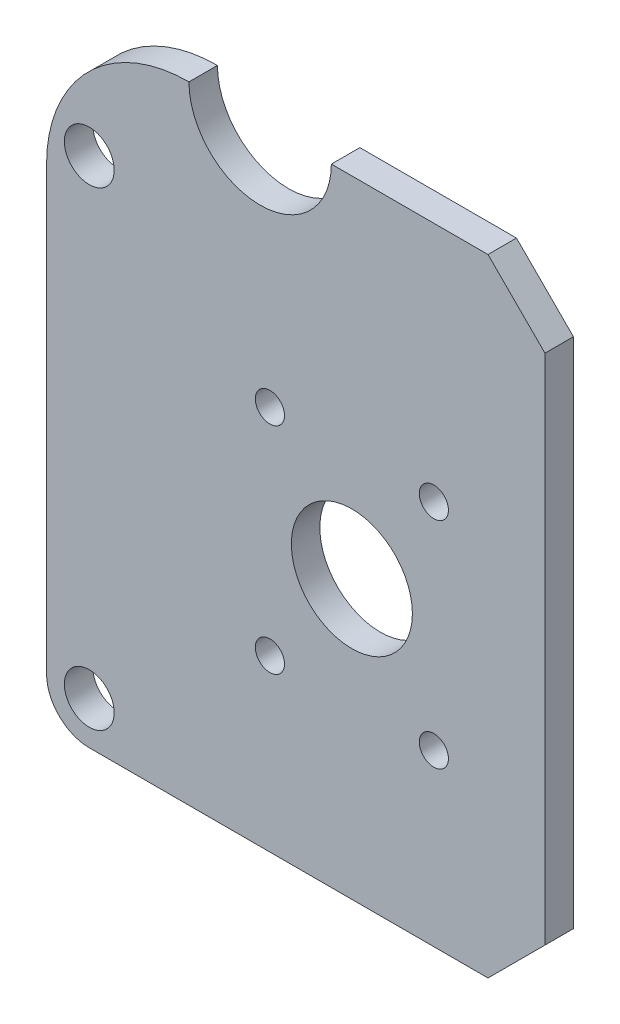
SolidWorks part; units mm, degrees
material "6061-T6 (SS)"
ref_plane "前视基准面" through (0, 0, 0) normal (0, 0, 1) x (1, 0, 0)
ref_plane "上视基准面" through (0, 0, 0) normal (0, 1, 0) x (1, 0, 0)
ref_plane "右视基准面" through (0, 0, 0) normal (1, 0, 0) x (0, 0, -1)
sketch "草图2" plane through (0, 0, 0) normal (0, 0, 1) x (1, 0, 0)
  line L0 (0, 19.5) -> (0, -19.5) construction
  line L1 (-18.5, 19.5) -> (18.5, 19.5)
  line L2 (-18.5, 19.5) -> (-18.5, -19.5)
  line L3 (-18.5, -19.5) -> (18.5, -19.5)
  line L4 (18.5, 19.5) -> (18.5, -19.5)
  dimension "D1" = 37
  dimension "D2" = 39
extrude "拉伸1" add sketch "草图2" along normal blind 2
sketch "草图3" plane through (0, 0, 2) normal (0, 0, 1) x (1, 0, 0)
  line L0 (-13.5, 16.5) -> (-13.5, -16.5) construction
  line L1 (0, 0) -> (-13.5, 0) construction
  line L2 (-18.5, 19.5) -> (-18.5, -19.5) construction
  circle A0 centre (-13.5, 16.5) radius 1.75
  circle A1 centre (-13.5, -16.5) radius 1.75
  dimension "D2" = 3.5
  dimension "D1" = 33
  dimension "D3" = 5
extrude "拉伸2" cut sketch "草图3" against normal blind 2
fillet "圆角1" [suppressed] radius 20
chamfer "倒角1" [suppressed] distance 22 angle 30
chamfer "倒角2" [suppressed] distance 22 angle 30
fillet "圆角2" [suppressed] radius 10
chamfer "倒角3" distance 1 angle 45 2 edges at (-18.5, -19.5, 1) (-18.5, 19.5, 1)
sketch "草图4" plane through (0, 0, 2) normal (0, 0, 1) x (1, 0, 0)
  line L0 (11.145, 5.2066) -> (-1.265, -5.2066) construction
  line L1 (4.94, 0) -> (4.94, 7.25) construction
  line L2 (-0.6138, 4.6602) -> (10.4938, -4.6602) construction
  line L3 (4.94, 0) -> (18.5, 0) construction
  line L5 (18.5, -19.5) -> (18.5, 19.5) construction
  circle A0 centre (4.94, 0) radius 8.1 construction
  circle A1 centre (4.94, 0) radius 7.25 construction
  circle A2 centre (-13.5, 16.5) radius 1.75 construction
  dimension "D1" = 16.2
  dimension "D2" = 14.5
  dimension "D3" = 50
  dimension "D4" = 50
  dimension "D5" = 18.44
hole_wizard "M1.6 螺纹孔1" [suppressed] positions "3D草图2" profile "草图6" tap size "M1.6" standard "GB"
sketch3d "3D草图2"
  point P3 (13.145, 5.2066, 2)
  point P6 (12.4938, -4.6602, 2)
  point P9 (0.735, -5.2066, 2)
  point P12 (1.3862, 4.6602, 2)
sketch "草图6" plane through (13.145, 5.2066, 2) normal (1, 0, 0) x (0, -1, 0)
  line L0 (0, 0) -> (0, 4.6255)
  line L1 (0, 4.6255) -> (0.625, 4.25)
  line L2 (0.625, 4.25) -> (0.625, 0)
  line L5 (0.625, 0) -> (0, 0)
  line L10 (0, 4.6255) -> (-0.625, 4.25) construction
  line L11 (0, -6.35) -> (0, 107.95) construction
  dimension "螺纹孔钻头直径" = 1.25
  dimension "螺纹孔钻头深度" = 4.25
  dimension "导头角度" = 118
cosmetic thread "Hole Thread1" [suppressed] parameters "D1"=2, "D2"=1.6
cosmetic thread "Hole Thread2" [suppressed] parameters "D1"=2, "D2"=1.6
cosmetic thread "Hole Thread3" [suppressed] parameters "D1"=2, "D2"=1.6
cosmetic thread "Hole Thread4" [suppressed] parameters "D1"=2, "D2"=1.6
sketch "草图7" plane through (0, 0, 2) normal (0, 0, 1) x (1, 0, 0)
  circle A0 centre (4.94, 0) radius 4.25
  dimension "D1" = 8.5
extrude "拉伸3" cut sketch "草图7" against normal blind 10
sketch "草图8" plane through (0, 0, 2) normal (0, 0, 1) x (1, 0, 0)
  line L0 (18.5, 19.5) -> (-17.5, 19.5) construction
  line L1 (-16.5, 19.5) -> (-18.5, 19.5)
  line L2 (-16.5, 19.5) -> (-16.5, -19.5)
  line L3 (-16.5, -19.5) -> (-18.5, -19.5)
  line L4 (-18.5, 19.5) -> (-18.5, -19.5)
  line L5 (-17.5, -19.5) -> (18.5, -19.5) construction
  line L6 (-18.5, 18.5) -> (-18.5, -18.5) construction
  dimension "D1" = 2
extrude "拉伸4" cut sketch "草图8" against normal blind 10
chamfer "倒角4" [suppressed] distance 1.5 angle 45
fillet "圆角3" radius 3 1 edges at (-16.5, -19.5, 1)
sketch "Sketch1" plane through (0, 0, 2) normal (0, 0, 1) x (1, 0, 0)
  line L0 (4.94, 0) -> (18.5, 0)
  line L1 (18.5, -19.5) -> (18.5, 19.5) construction
  line L2 (10.6969, 7.557) -> (-0.8169, -7.557)
  line L3 (-0.8169, 7.557) -> (10.6969, -7.557)
  dimension "D1" = 52.7
  dimension "D2" = 19
  dimension "D3" = 52.7
hole_wizard "M2.5 Tapped Hole1" positions "3DSketch1" profile "Sketch2" tap size "M2.5" standard "GB"
sketch3d "3DSketch1"
  point P0 (-0.8169, -7.557, 2)
  point P3 (10.6969, 7.557, 2)
  point P7 (-0.8169, 7.557, 2)
  point P10 (10.6969, -7.557, 2)
sketch "Sketch2" plane through (-0.8169, -7.557, 2) normal (1, 0, 0) x (0, -1, 0)
  line L0 (0, 0) -> (0, 7.8659)
  line L1 (0, 7.8659) -> (1.025, 7.25)
  line L2 (1.025, 7.25) -> (1.025, 0)
  line L5 (1.025, 0) -> (0, 0)
  line L10 (0, 7.8659) -> (-1.025, 7.25) construction
  line L11 (0, -6.35) -> (0, 107.95) construction
  dimension "Tap Drill Dia." = 2.05
  dimension "Tap Drill Depth" = 7.25
  dimension "Drill Angle" = 118
cosmetic thread "Hole Thread5" parameters "D1"=2, "D2"=2.5
cosmetic thread "Hole Thread6" parameters "D1"=2, "D2"=2.5
cosmetic thread "Hole Thread7" parameters "D1"=2, "D2"=2.5
cosmetic thread "Hole Thread8" parameters "D1"=2, "D2"=2.5
fillet "Fillet1" [suppressed] radius 3
sketch "Sketch3" [suppressed] plane through (0, 0, 2) normal (0, 0, 1) x (1, 0, 0)
  line L1 (19, 19.5) -> (15, 19.5)
  line L2 (19, 19.5) -> (19, 9.5)
  line L3 (19, 9.5) -> (15, 9.5)
  line L4 (15, 19.5) -> (15, 9.5)
  line L5 (19, -19.5) -> (15, -19.5)
  line L6 (19, -19.5) -> (19, -9.5)
  line L7 (19, -9.5) -> (15, -9.5)
  line L8 (15, -19.5) -> (15, -9.5)
  dimension "D1" = 10
  dimension "D2" = 4
extrude "Extrude1" [suppressed] cut sketch "Sketch3" against normal blind 10
chamfer "Chamfer1" [suppressed] distance 5 angle 45
fillet "Fillet2" [suppressed] radius 2.5
fillet "Fillet3" [suppressed] radius 2.5
fillet "Fillet4" [suppressed] radius 2.5
chamfer "Chamfer2" distance 4 angle 45 1 edges at (18.5, -19.5, 1)
sketch "草图9" plane through (0, 19.5, 0) normal (0, 1, 0) x (1, 0, 0)
  line L1 (-16.5, 0) -> (18.5, 0)
  line L2 (-16.5, 0) -> (-16.5, -2)
  line L3 (-16.5, -2) -> (18.5, -2)
  line L4 (18.5, 0) -> (18.5, -2)
extrude "凸台-拉伸1" add sketch "草图9" along normal blind 5
chamfer "倒角5" distance 4 angle 45 1 edges at (18.5, 24.5, 1)
fillet "圆角4" radius 10 1 edges at (-16.5, 24.5, 1)
sketch "草图11" plane through (0, 0, 2) normal (0, 0, 1) x (1, 0, 0)
  line L0 (-6.5, 24.5) -> (14.5, 24.5) construction
  circle A0 centre (-1.5, 24.5) radius 5
  dimension "D1" = 5
extrude "切除-拉伸1" cut sketch "草图11" against normal through all
